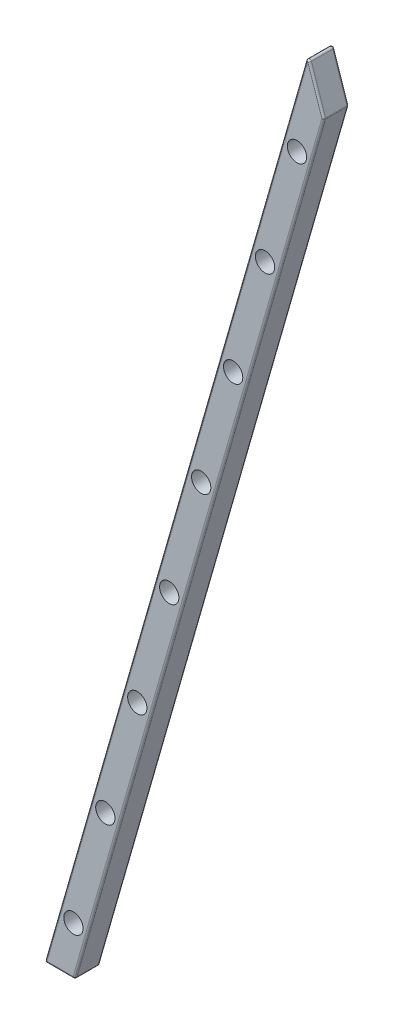
SolidWorks part; units mm, degrees
material "1023 Carbon Steel Sheet (SS)"
ref_plane "Ön Düzlem" through (0, 0, 0) normal (0, 0, 1) x (1, 0, 0)
ref_plane "Üst Düzlem" through (0, 0, 0) normal (0, 1, 0) x (1, 0, 0)
ref_plane "Sağ Düzlem" through (0, 0, 0) normal (1, 0, 0) x (0, 0, -1)
sketch "Sketch1" plane through (0, 0, 0) normal (0, 0, 1) x (1, 0, 0)
  line L0 (0, 0) -> (129.0354, 450)
  line L1 (129.0354, 450) -> (120.5996, 475)
  line L2 (120.5996, 475) -> (-15.6045, 0)
  line L3 (-15.6045, 0) -> (0, 0)
  line L4 (0, 0) -> (63.0446, 0) construction
  point P3 (163.7866, 450)
  point P7 (111.2802, 605.7616)
  point P8 (163.7866, 796.7132)
  point P9 (152.1752, 488.2776)
  point P10 (120.5996, 475)
  dimension "D1" = 74
  dimension "D2" = 450
  dimension "D3" = 25
  dimension "D4" = 15
extrude "Boss-Extrude1" add sketch "Sketch1" along normal mid plane 13
sketch "Sketch2" plane through (0, 0, 6.5) normal (0, 0, 1) x (1, 0, 0)
  line L6 (120.5996, 475) -> (-15.6045, 0) construction
  circle A12 centre (-0.6336, 25) radius 5
  circle A13 centre (15.9046, 82.6757) radius 5
  circle A14 centre (32.4429, 140.3514) radius 5
  circle A15 centre (48.9811, 198.0271) radius 5
  circle A16 centre (65.5194, 255.7028) radius 5
  circle A17 centre (82.0576, 313.3785) radius 5
  circle A18 centre (98.5958, 371.0542) radius 5
  circle A19 centre (115.1341, 428.7299) radius 5
  dimension "D1" = 10
  dimension "D2" = 7.5
  dimension "D3" = 25
  dimension "D5" = 82.6757
  dimension "D4" = 8
extrude "Cut-Extrude1" cut sketch "Sketch2" against normal through all both and the other way through all
fillet "Fillet1" radius 1 12 edges at (0, 0, 0) (64.5177, 225, 6.5) (129.0354, 450, 0) (64.5177, 225, -6.5) (-15.6045, 0, 0) (-7.8022, 0, -6.5) (-7.8022, 0, 6.5) (120.5996, 475, 0) (124.8175, 462.5, -6.5) (124.8175, 462.5, 6.5) (52.4975, 237.5, -6.5) (52.4975, 237.5, 6.5)
